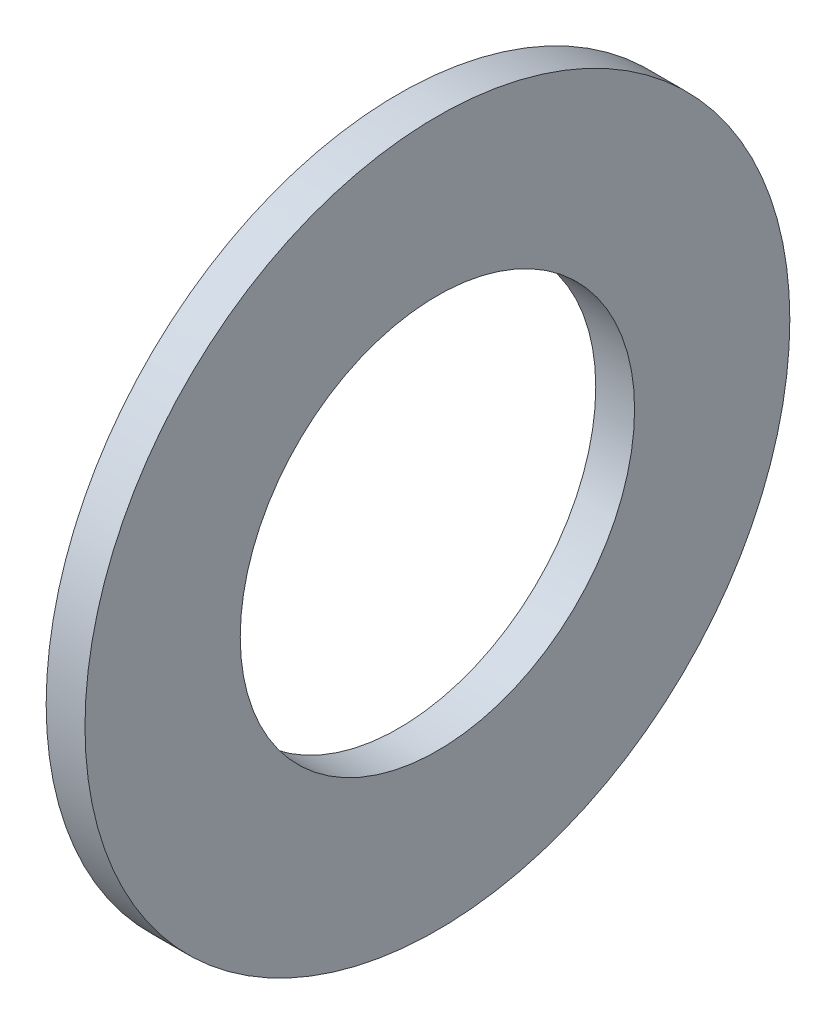
SolidWorks part; units mm, degrees
ref_plane "Front Plane" through (0, 0, 0) normal (0, 0, 1) x (1, 0, 0)
ref_plane "Top Plane" through (0, 0, 0) normal (0, 1, 0) x (1, 0, 0)
ref_plane "Right Plane" through (0, 0, 0) normal (1, 0, 0) x (0, 0, -1)
sketch "Sketch1" plane through (0, 0, 0) normal (1, 0, 0) x (0, 0, -1)
  circle A0 centre (0, 0) radius 45.4
  circle A1 centre (0, 0) radius 25.4
  dimension "D1" = 50.8
  dimension "D2" = 20
extrude "Boss-Extrude1" add sketch "Sketch1" along normal blind 5
